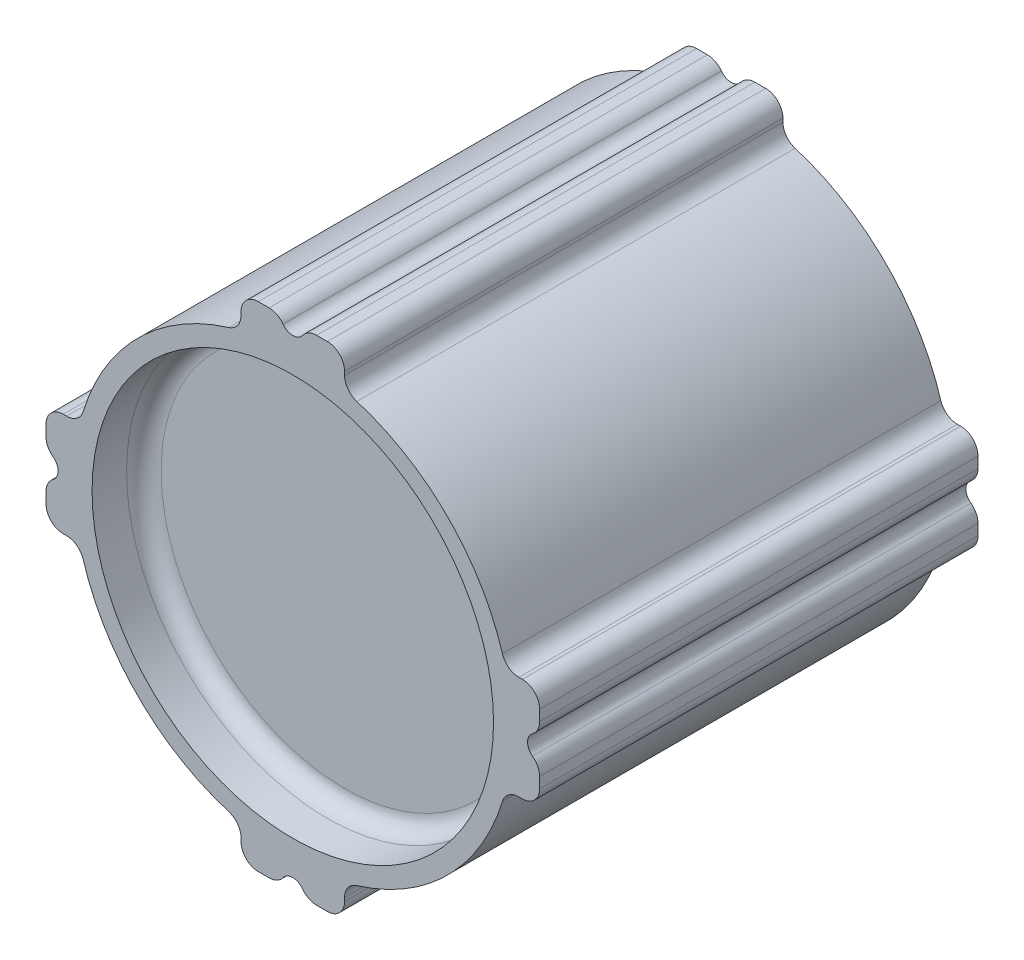
SolidWorks part; units mm, degrees
ref_plane "Front Plane" through (0, 0, 0) normal (0, 0, 1) x (1, 0, 0)
ref_plane "Top Plane" through (0, 0, 0) normal (0, 1, 0) x (1, 0, 0)
ref_plane "Right Plane" through (0, 0, 0) normal (1, 0, 0) x (0, 0, -1)
sketch "Sketch1" plane through (0, 0, 0) normal (0, 0, 1) x (1, 0, 0)
  circle A0 centre (0, 0) radius 6.35
  dimension "D1" = 12.7
sketch "Sketch2" plane through (0, 0, 0) normal (0, 0, 1) x (1, 0, 0)
  line L1 (-7.15, -1.5) -> (7.15, -1.5)
  line L2 (-7.15, -1.5) -> (-7.15, 1.5)
  line L3 (-7.15, 1.5) -> (7.15, 1.5)
  line L4 (7.15, -1.5) -> (7.15, 1.5)
  line L5 (-7.15, -1.5) -> (7.15, 1.5) construction
  line L6 (-7.15, 1.5) -> (7.15, -1.5) construction
  point P0 (0, 0)
  dimension "D1" = 14.3
  dimension "D2" = 3
extrude "Boss-Extrude1" add sketch "Sketch1" along normal blind 12.7
extrude "Boss-Extrude2" add sketch "Sketch2" along normal blind 12.7
sketch "Sketch3" plane through (0, 0, 0) normal (0, 0, 1) x (1, 0, 0)
  line L1 (-1.5, 7.15) -> (1.5, 7.15)
  line L2 (-1.5, 7.15) -> (-1.5, -7.15)
  line L3 (-1.5, -7.15) -> (1.5, -7.15)
  line L4 (1.5, 7.15) -> (1.5, -7.15)
  line L5 (-1.5, 7.15) -> (1.5, -7.15) construction
  line L6 (-1.5, -7.15) -> (1.5, 7.15) construction
  point P0 (0, 0)
  dimension "D1" = 14.3
  dimension "D2" = 3
extrude "Boss-Extrude3" add sketch "Sketch3" along normal blind 12.7
sketch "Sketch4" plane through (0, 0, 0) normal (0, 0, 1) x (1, 0, 0)
  line L0 (1.5, 7.15) -> (-1.5, 7.15) construction
  line L1 (7.15, -1.5) -> (7.15, 1.5) construction
  line L2 (-7.15, 1.5) -> (-7.15, -1.5) construction
  line L3 (-1.5, -7.15) -> (1.5, -7.15) construction
  circle A0 centre (0, 7.15) radius 0.35
  circle A1 centre (7.15, 0) radius 0.35
  circle A2 centre (-7.15, 0) radius 0.35
  circle A3 centre (0, -7.15) radius 0.35
  dimension "D1" = 0.7
  dimension "D2" = 0.7
  dimension "D3" = 0.7
  dimension "D4" = 0.7
extrude "Cut-Extrude2" cut sketch "Sketch4" along normal blind 12.7
fillet "Fillet1" radius 0.5 8 edges at (-7.15, -1.5, 6.35) (-1.5, -7.15, 6.35) (1.5, -7.15, 6.35) (7.15, -1.5, 6.35) (7.15, 1.5, 6.35) (1.5, 7.15, 6.35) (-1.5, 7.15, 6.35) (-7.15, 1.5, 6.35)
fillet "Fillet2" radius 0.5 16 edges at (-6.1703, 1.5, 6.35) (6.1703, 1.5, 6.35) (-1.5, 6.1703, 6.35) (-1.5, -6.1703, 6.35) (1.5, 6.1703, 6.35) (1.5, -6.1703, 6.35) (7.15, 0.35, 6.35) (7.15, -0.35, 6.35) (6.1703, -1.5, 6.35) (-6.1703, -1.5, 6.35) (0.35, -7.15, 6.35) (-0.35, -7.15, 6.35) (-0.35, 7.15, 6.35) (0.35, 7.15, 6.35) (-7.15, -0.35, 6.35) (-7.15, 0.35, 6.35)
sketch "Sketch5" plane through (0, 0, 0) normal (0, 0, 1) x (1, 0, 0)
  circle A0 centre (0, 0) radius 5.815
  dimension "D1" = 11.63
extrude "Cut-Extrude3" cut sketch "Sketch5" against normal blind 1.5 from offset 12.7
fillet "Fillet3" radius 0.5 1 edges at (5.815, 0, 11.2)
sketch "Sketch7" plane through (0, 0, 0) normal (0, 0, 1) x (1, 0, 0)
  circle A0 centre (0, 0) radius 3
  dimension "D1" = 6
extrude "Cut-Extrude5" cut sketch "Sketch7" along normal blind 9.5
sketch "Sketch8" plane through (0, 0, 0) normal (0, 0, 1) x (1, 0, 0)
  line L1 (-3, -3) -> (3, -3)
  line L2 (-3, -3) -> (-3, -1.44)
  line L3 (-3, -1.44) -> (3, -1.44)
  line L4 (3, -3) -> (3, -1.44)
  line L5 (-3, -3) -> (3, -1.44) construction
  line L6 (-3, -1.44) -> (3, -3) construction
  point P0 (0, -2.22)
  dimension "D1" = 3
  dimension "D2" = 6
  dimension "D3" = 0
  dimension "D4" = 1.44
extrude "Boss-Extrude4" add sketch "Sketch8" along normal blind 9.5 from offset 1
sketch "Sketch6" plane through (0, 0, 0) normal (0, 0, 1) x (1, 0, 0)
  circle A0 centre (0, 0) radius 5.565
  dimension "D1" = 11.13
extrude "Cut-Extrude4" cut sketch "Sketch6" along normal blind 4.5
